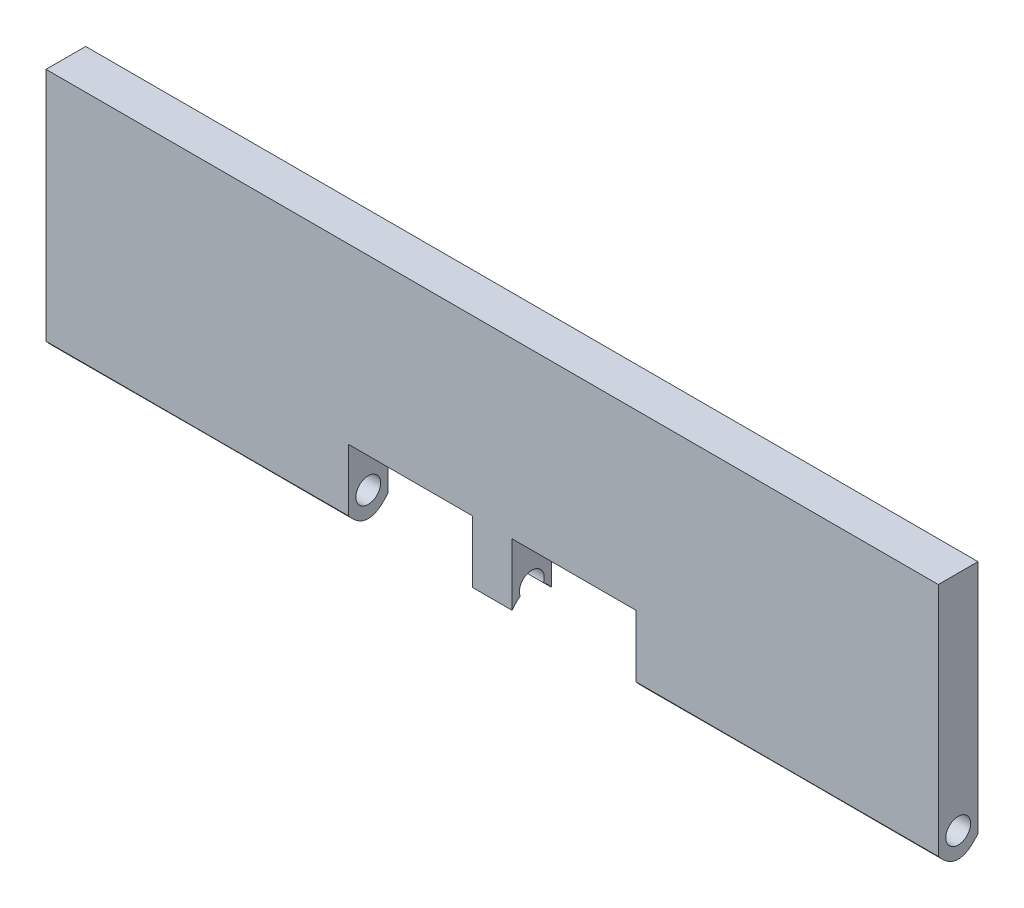
SolidWorks part; units mm, degrees
ref_plane "Plan de face" through (0, 0, 0) normal (0, 0, 1) x (1, 0, 0)
ref_plane "Plan de dessus" through (0, 0, 0) normal (0, 1, 0) x (1, 0, 0)
ref_plane "Plan de droite" through (0, 0, 0) normal (1, 0, 0) x (0, 0, -1)
sketch "Esquisse1" plane through (0, 0, 0) normal (0, 0, 1) x (1, 0, 0)
  line L0 (-29, -25) -> (-29, -10)
  line L1 (-90, -25) -> (-29, -25)
  line L2 (-90, -25) -> (-90, 25)
  line L3 (-90, 25) -> (90, 25)
  line L4 (90, -25) -> (90, 25)
  line L5 (-90, -25) -> (90, 25) construction
  line L6 (-90, 25) -> (90, -25) construction
  line L7 (-29, -10) -> (-4, -10)
  line L8 (-4, -10) -> (-4, -25)
  line L9 (0, 0) -> (0, -25) construction
  line L10 (-4, -25) -> (4, -25)
  line L11 (4, -10) -> (4, -25)
  line L12 (29, -10) -> (4, -10)
  line L13 (29, -25) -> (29, -10)
  line L14 (29, -25) -> (90, -25)
  point P0 (0, 0)
  dimension "D1" = 180
  dimension "D2" = 50
  dimension "D3" = 25
  dimension "D4" = 4
  dimension "D5" = 15
extrude "Boss.-Extru.1" add sketch "Esquisse1" along normal blind 8
sketch "Esquisse2" plane through (-90, 0, 0) normal (-1, 0, 0) x (0, 0, 1)
  line L0 (4, -25) -> (4, -8.5674) construction
  line L1 (8, -25) -> (0, -25) construction
  line L2 (4, -22.5) -> (0, -22.5) construction
  line L3 (0, 25) -> (0, -25) construction
  line L4 (8, 25) -> (8, -25) construction
  line L5 (0, -22.5) -> (0, -25)
  line L6 (0, -25) -> (8, -25)
  line L7 (8, -25) -> (8, -22.5)
  circle A0 centre (4, -20) radius 2.5
  spline S0 degree 2 poles (0, -22.5) (4, -27.5) (8, -22.5) knots 0 0 0 1 1 1
  line M1 (0, 25) -> (0, -25)
  line M2 (0, -25) -> (8, -25)
  line M3 (8, -25) -> (8, 25)
  dimension "D1" = 5
  dimension "D2" = 5
extrude "Enlèv. mat.-Extru.1" cut sketch "Esquisse2" against normal up to surface (180 mm away) contours S0 L6 M3 | S0 M1 M2 | A0 up to face at (90, 0, 4)
sketch "Esquisse4" plane through (0, 0, 0) normal (1, 0, 0) x (0, 0, -1)
  line L0 (0, 0) -> (5, 0) construction
  line L1 (5, 4.5) -> (0, 4.5)
  line L2 (0, 25) -> (0, -22.5) construction
  line L3 (5, -4.5) -> (0, -4.5)
  line L4 (0, 4.5) -> (0, -4.5)
  circle A0 centre (5, 0) radius 2.5
  arc A1 (5, -4.5) -> (5, 4.5) centre (5, 0) ccw
  dimension "D1" = 5
  dimension "D2" = 2
  dimension "D3" = 5
extrude "Boss.-Extru.2" add sketch "Esquisse4" along normal blind 2.5 and the other way blind 2.5
sketch "Esquisse6" plane through (-4, 0, 0) normal (-1, 0, 0) x (0, 0, 1)
  parabola Q0 (8, -22.5) -> (0, -22.5) focus (4, -23.4) apex (4, -25) construction
  parabola Q1 (0, -22.5) -> (8, -22.5) focus (4, -23.4) apex (4, -25) construction
  spline S0 degree 2 poles (0, -22.5) (4, -17.5) (8, -22.5) knots 0 0 0 1 1 1
  spline S1 degree 2 poles (0, -22.5) (4, -27.5) (8, -22.5) knots 0 0 0 1 1 1
  point P0 (4, -20)
extrude "Enlèv. mat.-Extru.2" cut sketch "Esquisse6" against normal up to surface (8 mm away) up to face at (4, -22.5, 4)
